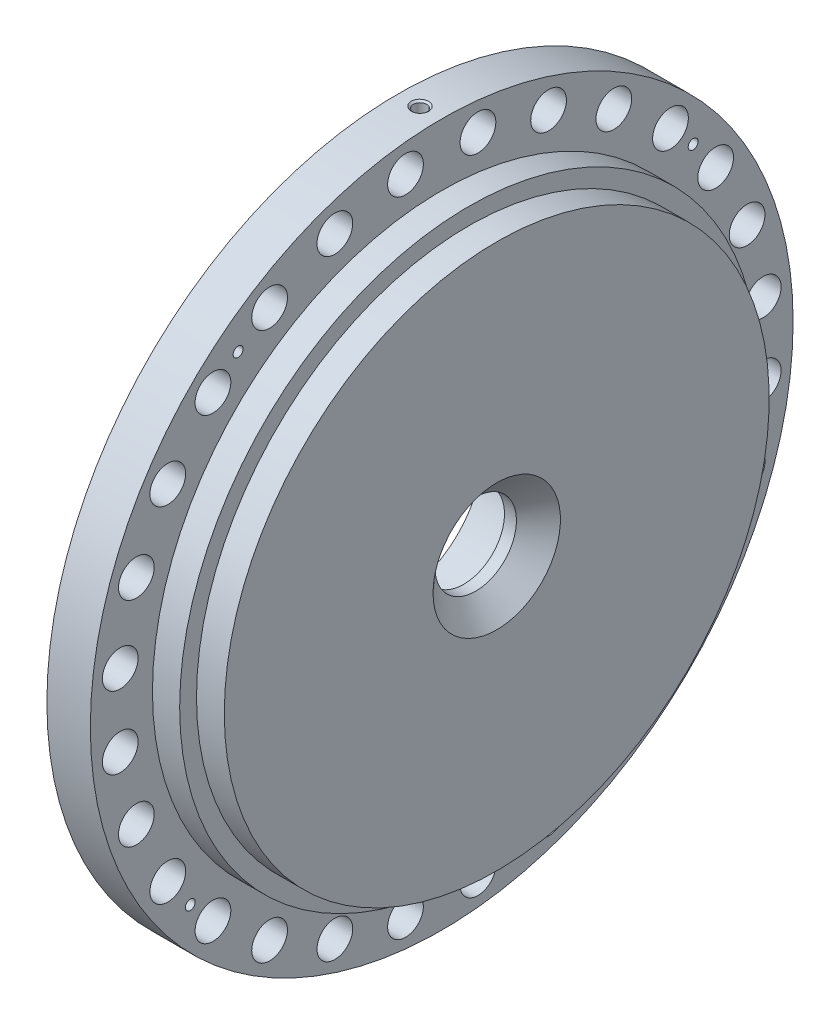
SolidWorks part; units mm, degrees
material "CD4Mc-U Duplex Stainless Steel"
ref_plane "Front Plane" through (0, 0, 0) normal (0, 0, 1) x (1, 0, 0)
ref_plane "Top Plane" through (0, 0, 0) normal (0, 1, 0) x (1, 0, 0)
ref_plane "Right Plane" through (0, 0, 0) normal (1, 0, 0) x (0, 0, -1)
sketch "Sketch1" plane through (0, 0, 0) normal (0, 0, 1) x (1, 0, 0)
  line L13 (-5.9944, 67.5005) -> (-5.9944, 180.9496)
  line L14 (-5.9944, 281.051) -> (28.7528, 281.051)
  line L15 (28.7528, 281.051) -> (28.7528, 231.3686)
  line L16 (28.7528, 231.3686) -> (50.5206, 231.3686)
  line L17 (50.5206, 231.3686) -> (50.5206, 217.9066)
  line L18 (50.5206, 217.9066) -> (72.7456, 217.9066)
  line L19 (72.7456, 217.9066) -> (72.7456, 50.9524)
  line L22 (0, 0) -> (159.4613, 0) construction
  line L27 (-5.9944, 228.9937) -> (0, 228.9937)
  line L28 (0, 228.9937) -> (0, 180.9496)
  line L29 (0, 180.9496) -> (-5.9944, 180.9496)
  line L30 (-5.9944, 228.9937) -> (-5.9944, 281.051)
  line L32 (-5.9944, 67.5005) -> (46.4058, 67.5005)
  line L35 (46.4058, 67.5005) -> (46.4058, 32.5628)
  line L36 (46.4058, 32.5628) -> (55.9308, 32.5628)
  line L37 (55.9308, 32.5628) -> (72.7456, 50.9524)
  dimension "D1" = 78.74
  dimension "D2" = 43.9928
  dimension "D3" = 21.7678
  dimension "D4" = 9.525
  dimension "D5" = 281.051
  dimension "D6" = 228.9937
  dimension "D7" = 231.3686
  dimension "D8" = 217.9066
  dimension "D9" = 180.9496
  dimension "D11" = 5.9944
  dimension "D12" = 32.5628
  dimension "D13" = 52.4002
  dimension "D14" = 67.5005
  dimension "D16" = 50.9524
revolve "Revolve1" add sketch "Sketch1" angle 360 about L22
sketch "Sketch4" plane through (-5.9944, 0, 0) normal (-1, 0, 0) x (0, 0, 1)
  line L0 (0, 0) -> (0, 281.051) construction
  line L1 (0, 0) -> (28.9721, 257.1355) construction
  circle A1 centre (28.9721, 257.1355) radius 14.2875
  circle A2 centre (0, 0) radius 258.7625 construction
  dimension "D2" = 28.575
  dimension "D3" = 517.525
  dimension "D1" = 6.429
extrude "Cut-Extrude1" cut sketch "Sketch4" against normal through all
pattern_circular "CirPattern2" count 28 over 360 about axis through (0, 0, 0) along (1, 0, 0) of "Cut-Extrude1"
sketch "Sketch5" plane through (0, 0, 0) normal (-1, 0, 0) x (0, 0, 1)
  line L0 (0, 0) -> (166.4902, 121.9494) construction
  line L2 (0, 0) -> (176.0245, 219.1005) construction
  circle A0 centre (0, 0) radius 206.375 construction
  circle A1 centre (166.4902, 121.9494) radius 9.525
  circle A3 centre (0, 0) radius 281.051 construction
  dimension "D1" = 412.75
  dimension "D3" = 19.05
  dimension "D2" = 15
hole_wizard "3/4-10 Tapped Hole1" positions "Sketch7" profile "Sketch8" tap size "3/4-10" standard "ANSI Inch"
sketch "Sketch7" plane through (0, 0, 0) normal (-1, 0, 0) x (0, 0, 1)
  point P0 (166.4902, 121.9494)
sketch "Sketch8" plane through (0, 121.9494, 166.4902) normal (0, 1, 0) x (0, 0, 1)
  line L0 (0, 0) -> (0, 30.4074)
  line L1 (0, 30.4074) -> (8.3337, 25.4)
  line L2 (8.3337, 25.4) -> (8.3337, 1.8263)
  line L3 (8.3337, 1.8263) -> (10.16, 0)
  line L5 (10.16, 0) -> (0, 0)
  line L6 (-8.3337, 1.8263) -> (-10.16, 0) construction
  line L10 (0, 30.4074) -> (-8.3337, 25.4) construction
  line L11 (0, -6.35) -> (0, 107.95) construction
  dimension "Tap Drill Dia." = 16.6675
  dimension "Tap Drill Depth" = 25.4
  dimension "Near C'Sink Dia." = 20.32
  dimension "Near C'Sink Angle" = 90
  dimension "Drill Angle" = 118
cosmetic thread "Hole Thread2" parameters "D1"=12.7, "D2"=19.05
pattern_circular "CirPattern3" count 12 over 360 about axis through (0, 0, 0) along (1, 0, 0) of "3/4-10 Tapped Hole1"
cosmetic thread "Hole Thread3" parameters "D1"=12.7, "D2"=19.05
cosmetic thread "Hole Thread4" parameters "D1"=12.7, "D2"=19.05
cosmetic thread "Hole Thread5" parameters "D1"=12.7, "D2"=19.05
cosmetic thread "Hole Thread6" parameters "D1"=12.7, "D2"=19.05
cosmetic thread "Hole Thread7" parameters "D1"=12.7, "D2"=19.05
cosmetic thread "Hole Thread8" parameters "D1"=12.7, "D2"=19.05
cosmetic thread "Hole Thread9" parameters "D1"=12.7, "D2"=19.05
cosmetic thread "Hole Thread10" parameters "D1"=12.7, "D2"=19.05
cosmetic thread "Hole Thread11" parameters "D1"=12.7, "D2"=19.05
cosmetic thread "Hole Thread12" parameters "D1"=12.7, "D2"=19.05
cosmetic thread "Hole Thread13" parameters "D1"=12.7, "D2"=19.05
sketch "Sketch9" plane through (-5.9944, 0, 0) normal (-1, 0, 0) x (0, 0, 1)
  line L0 (0, 0) -> (0, 94.996) construction
  line L1 (0, 0) -> (67.1723, 67.1723) construction
  circle A0 centre (0, 0) radius 94.996 construction
  circle A1 centre (67.1723, 67.1723) radius 11.1125
  dimension "D1" = 189.992
  dimension "D3" = 22.225
  dimension "D2" = 45
hole_wizard "7/8-9 Tapped Hole1" positions "3DSketch1" profile "Sketch10" tap size "7/8-9" standard "ANSI Inch"
sketch3d "3DSketch1"
  point P0 (-5.9944, 67.1723, 67.1723)
sketch "Sketch10" plane through (-5.9944, 67.1723, 67.1723) normal (0, 1, 0) x (0, 0, 1)
  line L0 (0, 0) -> (0, 31.2422)
  line L1 (0, 31.2422) -> (9.7231, 25.4)
  line L2 (9.7231, 25.4) -> (9.7231, 2.0244)
  line L3 (9.7231, 2.0244) -> (11.7475, 0)
  line L5 (11.7475, 0) -> (0, 0)
  line L6 (-9.7231, 2.0244) -> (-11.7475, 0) construction
  line L10 (0, 31.2422) -> (-9.7231, 25.4) construction
  line L11 (0, -6.35) -> (0, 107.95) construction
  dimension "Tap Drill Dia." = 19.4462
  dimension "Tap Drill Depth" = 25.4
  dimension "Near C'Sink Dia." = 23.495
  dimension "Near C'Sink Angle" = 90
  dimension "Drill Angle" = 118
cosmetic thread "Hole Thread14" parameters "D1"=44.45, "D2"=22.225
pattern_circular "CirPattern4" count 4 over 360 about axis through (0, 0, 0) along (1, 0, 0) of "7/8-9 Tapped Hole1"
cosmetic thread "Hole Thread15" parameters "D1"=44.45, "D2"=22.225
cosmetic thread "Hole Thread16" parameters "D1"=44.45, "D2"=22.225
cosmetic thread "Hole Thread17" parameters "D1"=44.45, "D2"=22.225
sketch "Sketch11" plane through (-5.9944, 0, 0) normal (-1, 0, 0) x (0, 0, 1)
  line L0 (0, 0) -> (258.7625, 0) construction
  line L1 (0, 0) -> (201.0962, -162.8445) construction
  circle A0 centre (0, 0) radius 258.7625 construction
  circle A1 centre (201.0962, -162.8445) radius 4.7625
  dimension "D1" = 517.525
  dimension "D3" = 9.525
  dimension "D2" = 39
hole_wizard "Tap Drill for 3/8-16 Tap1" positions "3DSketch2" profile "Sketch12" hole size "3/8-16" standard "ANSI Inch"
sketch3d "3DSketch2"
  point P0 (-5.9944, -162.8445, 201.0962)
sketch "Sketch12" plane through (-5.9944, -162.8445, 201.0962) normal (0, 1, 0) x (0, 0, 1)
  line L0 (0, 0) -> (0, 43.0247)
  line L1 (0, 43.0247) -> (3.9687, 40.64)
  line L2 (3.9687, 40.64) -> (3.9687, 0.635)
  line L3 (3.9687, 0.635) -> (4.6037, 0)
  line L5 (4.6037, 0) -> (0, 0)
  line L6 (-3.9687, 0.635) -> (-4.6037, 0) construction
  line L10 (0, 43.0247) -> (-3.9688, 40.64) construction
  line L11 (0, -6.35) -> (0, 107.95) construction
  dimension "Hole Dia." = 7.9375
  dimension "Hole Depth" = 40.64
  dimension "Near C'Sink Dia." = 9.2075
  dimension "Near C'Sink Angle" = 90
  dimension "Drill Angle" = 118
pattern_circular "CirPattern5" count 4 over 360 about axis through (0, 0, 0) along (1, 0, 0) of "Tap Drill for 3/8-16 Tap1"
ref_plane "Plane2" through (0, 281.051, 0) normal (0, 1, 0) x (1, 0, 0)
sketch "Sketch20" plane through (0, 281.051, 0) normal (0, 1, 0) x (1, 0, 0)
  line L0 (-5.9944, 0) -> (11.3792, 0) construction
  line L1 (-5.9944, 281.051) -> (-5.9944, -281.051) construction
  dimension "D1" = 17.3736
hole_wizard "1/2-13 Tapped Hole4" positions "3DSketch8" profile "Sketch19" tap size "1/2-13" standard "ANSI Inch"
sketch3d "3DSketch8"
  point P0 (11.3792, 281.051, 0)
sketch "Sketch19" plane through (11.3792, 281.051, 0) normal (1, 0, 0) x (0, 0, 1)
  line L0 (0, 0) -> (0, 38.2715)
  line L1 (0, 38.2715) -> (5.3581, 35.052)
  line L2 (5.3581, 35.052) -> (5.3581, 1.3651)
  line L3 (5.3581, 1.3651) -> (6.985, 0)
  line L5 (6.985, 0) -> (0, 0)
  line L6 (-5.3581, 1.3651) -> (-6.985, 0) construction
  line L10 (0, 38.2715) -> (-5.3581, 35.052) construction
  line L11 (0, -6.35) -> (0, 107.95) construction
  dimension "Tap Drill Dia." = 10.7163
  dimension "Tap Drill Depth" = 35.052
  dimension "Near C'Sink Dia." = 13.97
  dimension "Near C'Sink Angle" = 100
  dimension "Drill Angle" = 118
cosmetic thread "Hole Thread24" parameters "D1"=25.4, "D2"=12.7
